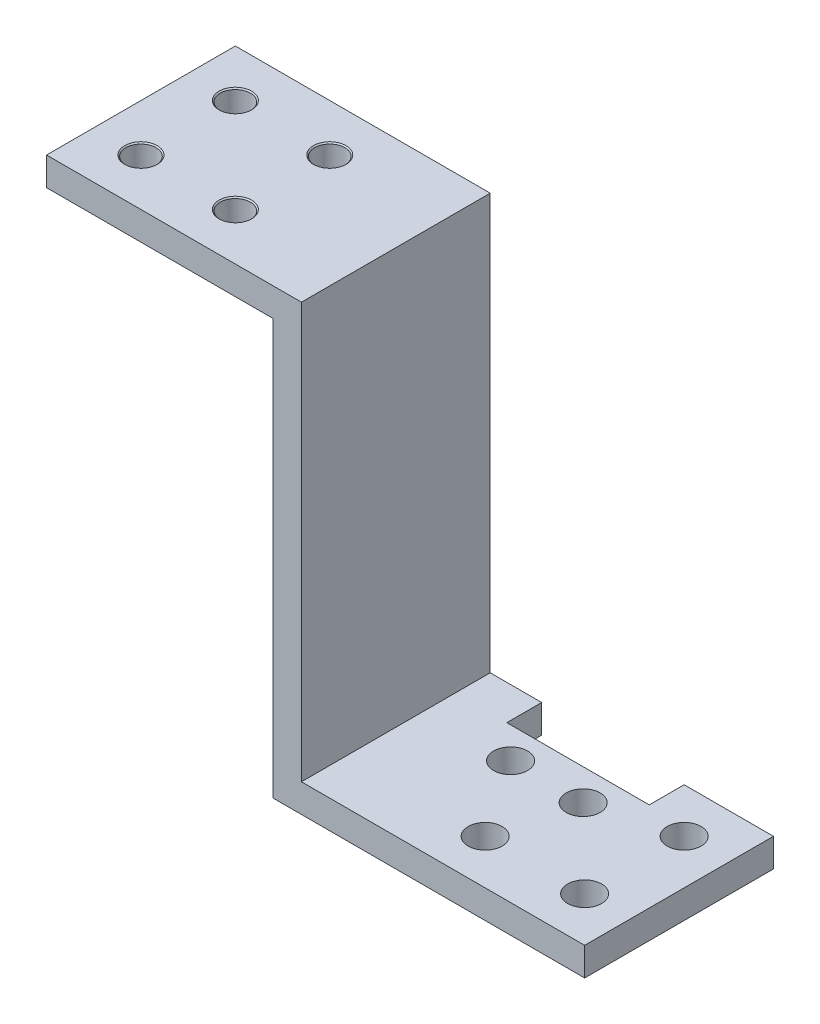
SolidWorks part; units mm, degrees
ref_plane "Front Plane" through (0, 0, 0) normal (0, 0, 1) x (1, 0, 0)
ref_plane "Top Plane" through (0, 0, 0) normal (0, 1, 0) x (1, 0, 0)
ref_plane "Right Plane" through (0, 0, 0) normal (1, 0, 0) x (0, 0, -1)
sketch "Sketch1" plane through (0, 0, 0) normal (0, 0, 1) x (1, 0, 0)
  line L0 (0, 44) -> (24, 44)
  line L1 (24, 44) -> (24, 0)
  line L2 (24, 0) -> (57, 0)
  line L3 (57, 0) -> (57, 3)
  line L4 (57, 3) -> (27, 3)
  line L5 (27, 3) -> (27, 47)
  line L6 (27, 47) -> (0, 47)
  line L7 (0, 47) -> (0, 44)
  line L8 (24, 25) -> (27, 25) construction
  point P12 (27, 25)
  dimension "D1" = 3
  dimension "D2" = 24
  dimension "D3" = 44
  dimension "D4" = 30
extrude "Boss-Extrude1" add sketch "Sketch1" along normal blind 20
hole_wizard "M3 Clearance Hole1" positions "Sketch2" profile "Sketch3" hole size "M3" standard "ANSI Metric" end condition through all
sketch "Sketch2" plane through (0, 47, 0) normal (0, 1, 0) x (1, 0, 0)
  line L0 (0, -10) -> (20, -10) construction
  line L1 (0, -20) -> (0, 0) construction
  line L4 (10, 0) -> (10, -20) construction
  line L7 (24, -20) -> (24, 0) construction
  line L8 (24, -20) -> (24, 0) construction
  line L9 (27, -20) -> (0, -20) construction
  point P17 (5, -5)
  point P25 (5, -15)
  point P26 (15, -5)
  point P27 (15, -15)
  point P37 (10, -10)
  dimension "D1" = 5
  dimension "D2" = 5
  dimension "D3" = 20
sketch "Sketch3" plane through (15, 47, 15) normal (1, 0, 0) x (0, 0, 1)
  line L0 (0, 0) -> (0, 47)
  line L1 (0, 47) -> (1.6, 47)
  line L2 (1.6, 47) -> (1.6, 0.125)
  line L3 (1.6, 0.125) -> (1.725, 0)
  line L5 (1.725, 0) -> (0, 0)
  line L6 (-1.6, 0.125) -> (-1.725, 0) construction
  line L11 (0, -6.35) -> (0, 107.95) construction
  dimension "Thru Hole Dia." = 3.2
  dimension "Thru Hole Depth" = 47
  dimension "Near C'Sink Dia." = 3.45
  dimension "Near C'Sink Angle" = 90
sketch "Sketch4" plane through (0, 3, 0) normal (0, 1, 0) x (1, 0, 0)
  line L0 (57, 0) -> (27, 0) construction
  line L1 (32.4508, 0) -> (47.5398, 0)
  line L2 (32.4508, 0) -> (32.4508, -3.6956)
  line L3 (32.4508, -3.6956) -> (47.5398, -3.6956)
  line L4 (47.5398, 0) -> (47.5398, -3.6956)
  line L5 (32.6508, -10.4956) -> (32.6508, -3.4956) construction
  line L6 (47.3398, -10.4956) -> (47.3398, -3.4956) construction
  line L7 (32.6508, -10.4956) -> (32.6508, -3.4956) construction
  line L8 (47.3398, -10.4956) -> (47.3398, -3.4956) construction
  line L9 (32.6508, -3.4956) -> (47.3398, -3.4956) construction
  point P10 (39.9953, -3.6956)
  point P11 (39.9953, -3.4956)
  dimension "D1" = 0.2
  dimension "D2" = 0.2
extrude "Cut-Extrude1" cut sketch "Sketch4" against normal through all
sketch "Sketch5" plane through (0, 3, 0) normal (0, 1, 0) x (1, 0, 0)
  point P0 (36.1508, -6.9956)
  point P3 (43.8398, -6.9956)
hole_wizard "M3 Clearance Hole2" positions "Sketch5" profile "Sketch6" hole size "M3" standard "ANSI Metric" end condition through all
sketch "Sketch6" plane through (36.1508, 3, 6.9956) normal (1, 0, 0) x (0, 0, 1)
  line L0 (0, 0) -> (0, 3)
  line L1 (0, 3) -> (1.8, 3)
  line L2 (1.8, 3) -> (1.8, 0)
  line L5 (1.8, 0) -> (0, 0)
  line L11 (0, -6.35) -> (0, 107.95) construction
  dimension "Thru Hole Dia." = 3.6
  dimension "Thru Hole Depth" = 3
sketch "Sketch9" plane through (0, 3, 0) normal (0, 1, 0) x (1, 0, 0)
  line L0 (57, -20) -> (27, -20) construction
  line L1 (57, -20) -> (57, 0) construction
  line L2 (57, 0) -> (47.5398, 0) construction
  line L3 (47.5398, -3.6956) -> (47.5398, 0) construction
  line L4 (57, -20) -> (27, -20)
  line L5 (57, -20) -> (57, 0)
  line L6 (57, 0) -> (47.5398, 0)
  line L7 (47.5398, -3.6956) -> (47.5398, 0)
  line L8 (47.5398, -3.6956) -> (47.5398, -10.5398)
  line L9 (47.5398, -10.5398) -> (37, -10.5398)
  line L10 (37, -10.5398) -> (37, -20)
  line L11 (52.2699, 0) -> (52.2699, -4.7301) construction
  line L12 (52.2699, -4.7301) -> (52.2699, -15.2699) construction
  line L13 (52.2699, -15.2699) -> (52.2699, -20) construction
  line L14 (37, -15.2699) -> (41.7301, -15.2699) construction
  line L15 (41.7301, -15.2699) -> (52.2699, -15.2699) construction
  line L16 (52.2699, -15.2699) -> (57, -15.2699) construction
  circle A0 centre (52.2699, -4.7301) radius 1.75
  circle A1 centre (52.2699, -15.2699) radius 1.75
  circle A2 centre (41.7301, -15.2699) radius 1.75
  point P11 (52.2699, 0)
  point P18 (37, -15.2699)
  dimension "D1" = 3.5
  dimension "D2" = 3.5
  dimension "D3" = 3.5
sketch "Sketch10" plane through (0, 3, 0) normal (0, 1, 0) x (1, 0, 0)
  point P0 (41.7301, -15.2699)
  point P3 (52.2699, -15.2699)
  point P6 (52.2699, -4.7301)
hole_wizard "M3 Clearance Hole3" positions "Sketch10" profile "Sketch11" hole size "M3" standard "ANSI Metric" end condition through all
sketch "Sketch11" plane through (41.7301, 3, 15.2699) normal (1, 0, 0) x (0, 0, 1)
  line L0 (0, 0) -> (0, 3)
  line L1 (0, 3) -> (1.8, 3)
  line L2 (1.8, 3) -> (1.8, 0)
  line L5 (1.8, 0) -> (0, 0)
  line L11 (0, -6.35) -> (0, 107.95) construction
  dimension "Thru Hole Dia." = 3.6
  dimension "Thru Hole Depth" = 3
